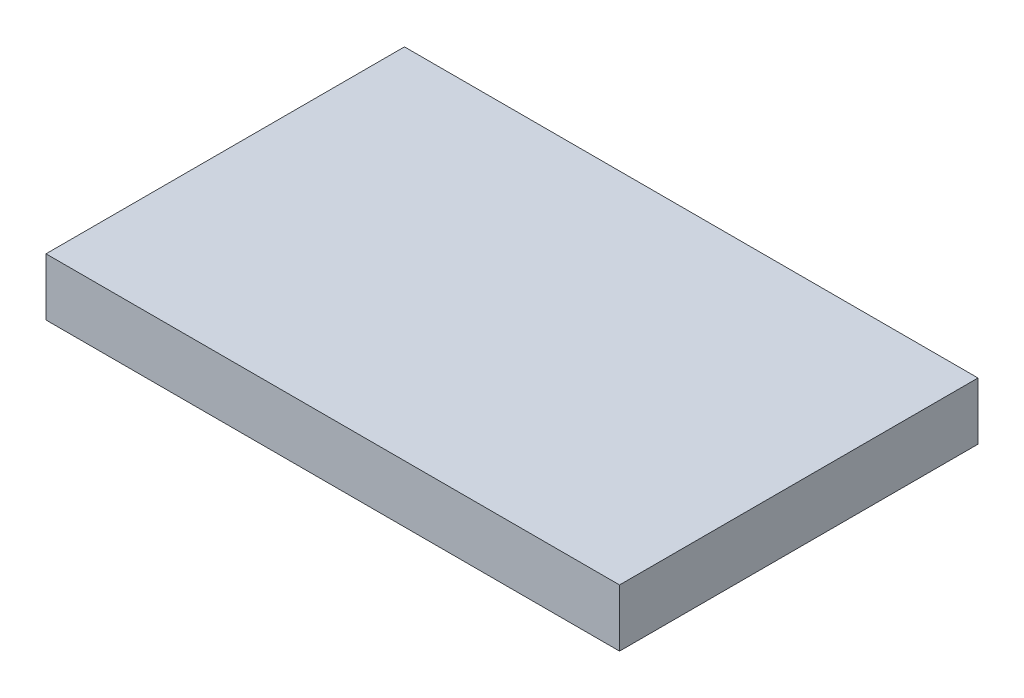
SolidWorks part; units mm, degrees
ref_plane "Front Plane" through (0, 0, 0) normal (0, 0, 1) x (1, 0, 0)
ref_plane "Top Plane" through (0, 0, 0) normal (0, 1, 0) x (1, 0, 0)
ref_plane "Right Plane" through (0, 0, 0) normal (1, 0, 0) x (0, 0, -1)
sketch "Sketch1" plane through (0, 0, 0) normal (0, 1, 0) x (1, 0, 0)
  line L1 (0, 0) -> (20, 0)
  line L2 (0, 0) -> (0, -12.5)
  line L3 (0, -12.5) -> (20, -12.5)
  line L4 (20, 0) -> (20, -12.5)
  dimension "D1" = 12.5
  dimension "D2" = 20
extrude "Boss-Extrude1" add sketch "Sketch1" along normal blind 2
